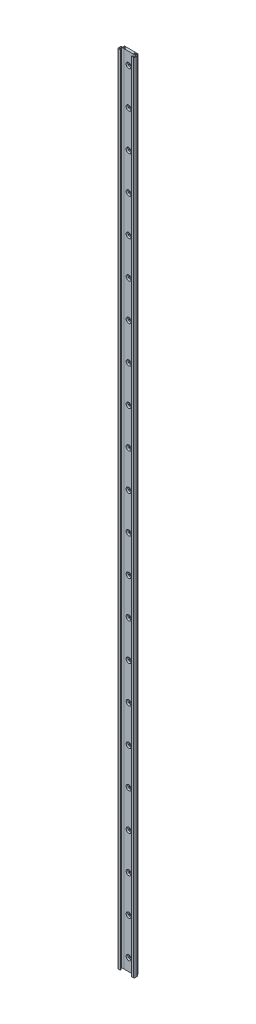
SolidWorks part; units mm, degrees
ref_plane "Plan de face" through (0, 0, 0) normal (0, 0, 1) x (1, 0, 0)
ref_plane "Plan de dessus" through (0, 0, 0) normal (0, 1, 0) x (1, 0, 0)
ref_plane "Plan de droite" through (0, 0, 0) normal (1, 0, 0) x (0, 0, -1)
ref_plane "Plan1" through (0, 0, 0) normal (0, -1, 0) x (1, 0, 0)
sketch "Esquisse1" plane through (0, 0, 0) normal (0, -1, 0) x (1, 0, 0)
  line L0 (13.5, 3) -> (13.5, 8.7)
  line L1 (13.5, 8.7) -> (-13.5, 8.7)
  line L2 (-13.5, 8.7) -> (-13.5, 3)
  line L3 (-13.5, 3) -> (-7.8, 3)
  line L4 (-7.8, 1.5) -> (-11, 1.5)
  line L5 (-11, 1.5) -> (-11, 0)
  line L6 (-11, 0) -> (11, 0)
  line L7 (11, 0) -> (11, 1.5)
  line L8 (11, 1.5) -> (7.8, 1.5)
  line L9 (7.8, 3) -> (13.5, 3)
  arc A0 (-7.8, 3) -> (-7.8, 1.5) centre (-7.8, 2.25) cw
  arc A1 (7.8, 1.5) -> (7.8, 3) centre (7.8, 2.25) cw
extrude "Boss.-Extru.1" add sketch "Esquisse1" against normal blind 1300
sketch "Esquisse2" plane through (0, 1300, 0) normal (0, 1, 0) x (-1, 0, 0)
  line L0 (8.75, 8.7) -> (-8.75, 8.7)
  line L1 (-8.75, 8.7) -> (-8.75, 7.6)
  line L2 (-8.75, 7.6) -> (-12, 7.6)
  line L3 (-12, 7.6) -> (-12, 4.1)
  line L4 (-12, 4.1) -> (12, 4.1)
  line L5 (12, 4.1) -> (12, 7.6)
  line L6 (12, 7.6) -> (8.75, 7.6)
  line L7 (8.75, 7.6) -> (8.75, 8.7)
extrude "Enlèv. mat.-Extru.1" cut sketch "Esquisse2" against normal through all
hole_wizard "Diamètre du perçage Ø0.4 (0.4)1" positions "Esquisse4" profile "Esquisse3" hole size "Ø0.4" standard "Ansi Metric"
sketch "Esquisse4" plane through (0, 0, 0) normal (0, -1, 0) x (-1, 0, 0)
  point P0 (7.75, -4.1)
  point P1 (-7.75, -4.1)
sketch "Esquisse3" plane through (-7.75, 0, 4.1) normal (1, 0, 0) x (0, 0, -1)
  line L0 (0, 0) -> (0, 1300)
  line L1 (0, 1300) -> (0.2, 1300)
  line L2 (0.2, 1300) -> (0.2, 0)
  line L5 (0.2, 0) -> (0, 0)
  line L11 (0, -6.35) -> (0, 107.95) construction
  dimension "Diamètre du perçage jusqu'au prochain" = 0.4
  dimension "Profondeur du perçage jusqu'au prochain" = 1300
hole_wizard "Chambrage pour vis à tête hexagonale M41" positions "Esquisse6" profile "Esquisse5" counterbore size "M4" standard "Ansi Metric"
sketch "Esquisse6" plane through (0, 0, 4.1) normal (0, 0, 1) x (1, 0, 0)
  point P0 (0, 20)
  point P1 (0, 80)
sketch "Esquisse5" plane through (0, 20, 4.1) normal (1, 0, 0) x (0, -1, 0)
  line L0 (0, 0) -> (0, 4.1)
  line L1 (0, 4.1) -> (2.25, 4.1)
  line L3 (2.25, 4.1) -> (2.25, 3.1)
  line L4 (2.25, 3.1) -> (4.25, 3.1)
  line L5 (4.25, 3.1) -> (4.25, 0)
  line L7 (4.25, 0) -> (0, 0)
  line L11 (0, -6.35) -> (0, 107.95) construction
  dimension "Diamètre du perçage jusqu'au prochain" = 4.5
  dimension "Profondeur du perçage jusqu'au prochain" = 4.1
  dimension "Diamètre du chambrage" = 8.5
  dimension "Profondeur du chambrage" = 3.1
fillet "Congé1" radius 0.2 2 edges at (11, 650, 1.5) (-11, 650, 1.5)
fillet "Congé2" radius 0.5 4 edges at (12, 650, 7.6) (-12, 650, 7.6) (-12, 650, 4.1) (12, 650, 4.1)
fillet "Congé3" radius 1 4 edges at (-13.5, 650, 3) (13.5, 650, 3) (-13.5, 650, 8.7) (13.5, 650, 8.7)
pattern_linear "Répétition linéaire1" count 21 spacing 60 along (0, 1, 0) of "Chambrage pour vis à tête hexagonale M41"
